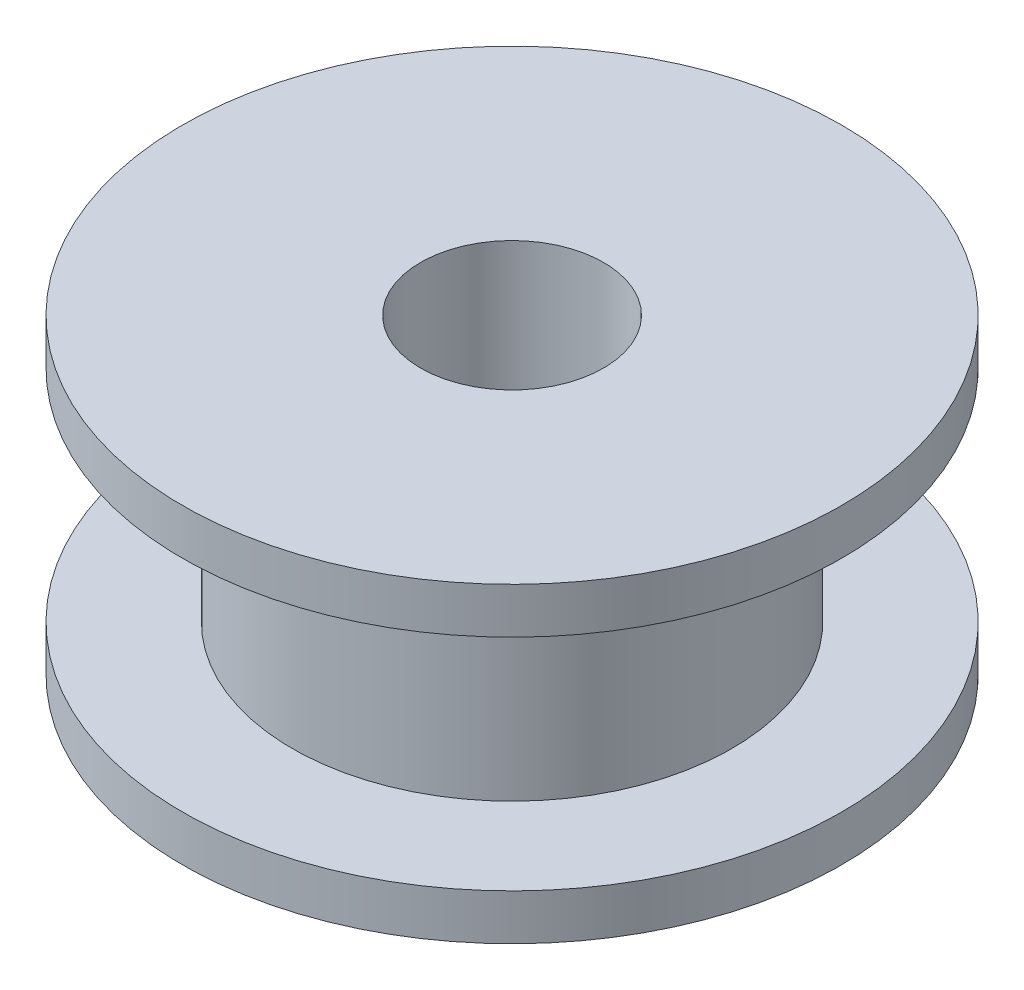
SolidWorks part; units mm, degrees
ref_plane "前视基准面" through (0, 0, 0) normal (0, 0, 1) x (1, 0, 0)
ref_plane "上视基准面" through (0, 0, 0) normal (0, 1, 0) x (1, 0, 0)
ref_plane "右视基准面" through (0, 0, 0) normal (1, 0, 0) x (0, 0, -1)
sketch "草图1" plane through (0, 0, 0) normal (0, 0, 1) x (1, 0, 0)
  line L0 (0, 0) -> (22.0862, 0) construction
  line L1 (0, 0) -> (0, 11.2679) construction
  line L2 (0, -8.5) -> (-9, -8.5)
  line L3 (-9, -8.5) -> (-9, -7.25)
  line L4 (-9, -7.25) -> (-6, -7.25)
  line L5 (-6, -7.25) -> (-6, -1.25)
  line L6 (-6, -1.25) -> (-9, -1.25)
  line L7 (-9, -1.25) -> (-9, 0)
  line L8 (-9, 0) -> (0, 0)
  line L9 (0, 0) -> (0, -8.5)
  point P2 (0, 0)
  dimension "D1" = 9
  dimension "D2" = 8.5
  dimension "D3" = 6
  dimension "D4" = 6
revolve "旋转1" add sketch "草图1" angle 360 about L1
sketch "草图2" plane through (0, 0, 0) normal (0, 1, 0) x (1, 0, 0)
  circle A0 centre (0, 0) radius 2.5
  dimension "D1" = 5
extrude "切除-拉伸1" cut sketch "草图2" against normal blind 10
